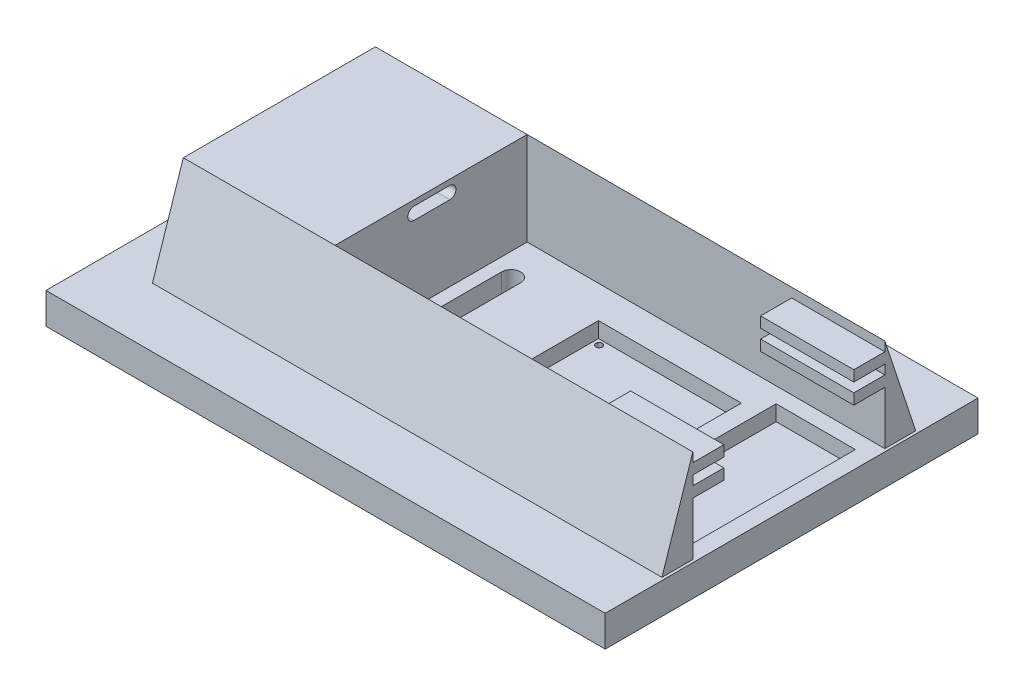
SolidWorks part; units mm, degrees
ref_plane "Front Plane" through (0, 0, 0) normal (0, 0, 1) x (1, 0, 0)
ref_plane "Top Plane" through (0, 0, 0) normal (0, 1, 0) x (1, 0, 0)
ref_plane "Right Plane" through (0, 0, 0) normal (1, 0, 0) x (0, 0, -1)
sketch "Sketch1" plane through (0, 0, 0) normal (0, 1, 0) x (1, 0, 0)
  line L1 (90, 60) -> (-90, 60)
  line L2 (90, 60) -> (90, -60)
  line L3 (90, -60) -> (-90, -60)
  line L4 (-90, 60) -> (-90, -60)
  line L5 (90, 60) -> (-90, -60) construction
  line L6 (90, -60) -> (-90, 60) construction
  point P0 (0, 0)
  dimension "D1" = 120
  dimension "D2" = 180
extrude "Boss-Extrude1" add sketch "Sketch1" along normal blind 10
sketch "Sketch2" plane through (0, 10, 0) normal (0, 1, 0) x (1, 0, 0)
  line L1 (-26.0439, 30.9093) -> (-74.8883, 30.9093)
  line L2 (-26.0439, 30.9093) -> (-26.0439, -30.9093)
  line L3 (-26.0439, -30.9093) -> (-74.8883, -30.9093)
  line L4 (-74.8883, 30.9093) -> (-74.8883, -30.9093)
  line L5 (-26.0439, 30.9093) -> (-74.8883, -30.9093) construction
  line L6 (-26.0439, -30.9093) -> (-74.8883, 30.9093) construction
  point P0 (-50.4661, 0)
extrude "Boss-Extrude2" add sketch "Sketch2" along normal blind 30
sketch "Sketch3" plane through (-74.8883, 0, 0) normal (-1, 0, 0) x (0, 0, 1)
  line L0 (30.9093, 25) -> (0, 25) construction
  line L1 (30.9093, 40) -> (30.9093, 10) construction
  line L3 (13.5, 38.5) -> (-13.5, 38.5)
  line L4 (13.5, 38.5) -> (13.5, 11.5)
  line L5 (13.5, 11.5) -> (-13.5, 11.5)
  line L6 (-13.5, 38.5) -> (-13.5, 11.5)
  line L7 (13.5, 38.5) -> (-13.5, 11.5) construction
  line L8 (13.5, 11.5) -> (-13.5, 38.5) construction
  dimension "D1" = 27
  dimension "D2" = 27
extrude "Cut-Extrude1" cut sketch "Sketch3" against normal blind 10
sketch "Sketch4" plane through (-64.8883, 0, 0) normal (-1, 0, 0) x (0, 0, 1)
  line L0 (-6.0245, 37.2243) -> (5.5495, 37.2243) construction
  line L1 (-6.0245, 38.2264) -> (5.5495, 38.2264)
  line L2 (-6.0245, 36.2222) -> (5.5495, 36.2222)
  arc A0 (-6.0245, 38.2264) -> (-6.0245, 36.2222) centre (-6.0245, 37.2243) ccw
  arc A1 (5.5495, 36.2222) -> (5.5495, 38.2264) centre (5.5495, 37.2243) ccw
  point P2 (-0.2375, 37.2243)
extrude "Cut-Extrude5" cut sketch "Sketch4" against normal through all
hole_wizard "Tap Drill for M2.5 Tap1" positions "3DSketch2" profile "Sketch8" hole size "M2.5" standard "AS"
sketch3d "3DSketch2"
  point P0 (-64.8883, 36.9534, -12.0704)
  point P2 (-64.8883, 37.0029, 11.9892)
  point P4 (-64.8883, 13.0898, 11.9186)
  point P6 (-64.8883, 13.0898, -11.8428)
sketch "Sketch8" plane through (-64.8883, 36.9534, -12.0704) normal (0, 1, 0) x (0, 0, 1)
  line L0 (0, 0) -> (0, 5.6159)
  line L1 (0, 5.6159) -> (1.025, 5)
  line L2 (1.025, 5) -> (1.025, 0.0241)
  line L3 (1.025, 0.0241) -> (1.05, 0)
  line L5 (1.05, 0) -> (0, 0)
  line L6 (-1.025, 0.0241) -> (-1.05, 0) construction
  line L10 (0, 5.6159) -> (-1.025, 5) construction
  line L11 (0, -6.35) -> (0, 107.95) construction
  dimension "Hole Dia." = 2.05
  dimension "Hole Depth" = 5
  dimension "Near C'Sink Dia." = 2.1
  dimension "Near C'Sink Angle" = 92
  dimension "Drill Angle" = 118
sketch "Sketch9" plane through (0, 10, 0) normal (0, 1, 0) x (1, 0, 0)
  line L0 (-18.7936, -19.0798) -> (-18.7936, 18.5074) construction
  line L1 (-21.8464, -19.0798) -> (-21.8464, 18.5074)
  line L2 (-15.7408, -19.0798) -> (-15.7408, 18.5074)
  arc A0 (-21.8464, -19.0798) -> (-15.7408, -19.0798) centre (-18.7936, -19.0798) ccw
  arc A1 (-15.7408, 18.5074) -> (-21.8464, 18.5074) centre (-18.7936, 18.5074) ccw
  point P2 (-18.7936, -0.2862)
extrude "Cut-Extrude6" cut sketch "Sketch9" against normal through all
sketch "Sketch10" plane through (-74.8883, 0, 0) normal (-1, 0, 0) x (0, 0, 1)
  line L0 (30.9093, 10) -> (30.9093, 40)
  line L1 (30.9093, 40) -> (40.8472, 10)
  line L2 (-60, 10) -> (60, 10) construction
  line L3 (40.8472, 10) -> (30.9093, 10)
extrude "Boss-Extrude3" add sketch "Sketch10" against normal blind 49
mirror "Mirror2" about plane through (0, 0, 0) normal (0, 0, 1) of "Boss-Extrude3"
sketch "Sketch13" plane through (-25.8883, 0, 0) normal (1, 0, 0) x (0, 0, -1)
  line L0 (-30.9093, 10) -> (-40.8472, 10)
  line L1 (-60, 10) -> (60, 10) construction
  line L2 (-30.9093, 10) -> (-40.8472, 10) construction
  line L3 (-40.8472, 10) -> (-30.9093, 40)
  line L4 (-30.9093, 40) -> (-30.9093, 10)
sketch "Sketch14" plane through (0, 10, 0) normal (0, 1, 0) x (1, 0, 0)
  line L1 (53.3281, 20.5) -> (7.3281, 20.5)
  line L2 (53.3281, 20.5) -> (53.3281, -20.5)
  line L3 (53.3281, -20.5) -> (7.3281, -20.5)
  line L4 (7.3281, 20.5) -> (7.3281, -20.5)
  line L5 (53.3281, 20.5) -> (7.3281, -20.5) construction
  line L6 (53.3281, -20.5) -> (7.3281, 20.5) construction
  point P0 (30.3281, 0)
  dimension "D1" = 46
  dimension "D2" = 41
extrude "Cut-Extrude8" cut sketch "Sketch14" against normal blind 5
hole_wizard "Tap Drill for M2.5 Tap2" positions "3DSketch3" profile "Sketch17" hole size "M2.5" standard "AS"
sketch3d "3DSketch3"
  point P0 (9.5536, 5, 18.1965)
  point P2 (9.2777, 5, -18.7664)
  point P4 (51.5506, 5, -18.3527)
  point P6 (51.5506, 5, 18.7481)
sketch "Sketch17" plane through (9.5536, 5, 18.1965) normal (1, 0, 0) x (0, 0, 1)
  line L0 (0, 0) -> (0, 5.6159)
  line L1 (0, 5.6159) -> (1.025, 5)
  line L2 (1.025, 5) -> (1.025, 0.0241)
  line L3 (1.025, 0.0241) -> (1.05, 0)
  line L5 (1.05, 0) -> (0, 0)
  line L6 (-1.025, 0.0241) -> (-1.05, 0) construction
  line L10 (0, 5.6159) -> (-1.025, 5) construction
  line L11 (0, -6.35) -> (0, 107.95) construction
  dimension "Hole Dia." = 2.05
  dimension "Hole Depth" = 5
  dimension "Near C'Sink Dia." = 2.1
  dimension "Near C'Sink Angle" = 92
  dimension "Drill Angle" = 118
sketch "Sketch18" plane through (-25.8883, 0, 0) normal (1, 0, 0) x (0, 0, -1)
  line L0 (40.8472, 10) -> (30.9093, 10)
  line L1 (30.9093, 10) -> (30.9093, 40)
  line L2 (30.9093, 40) -> (40.8472, 10)
extrude "Boss-Extrude5" add sketch "Sketch18" along normal blind 115
sketch "Sketch19" plane through (-25.8883, 0, 0) normal (1, 0, 0) x (0, 0, -1)
  line L0 (-30.9093, 10) -> (-40.8472, 10)
  line L1 (-40.8472, 10) -> (-30.9093, 40)
  line L2 (-30.9093, 40) -> (-30.9093, 10)
extrude "Boss-Extrude6" add sketch "Sketch19" along normal blind 115
sketch "Sketch25" plane through (0, 0, 0) normal (0, -1, 0) x (1, 0, 0)
  line L0 (-90, 60) -> (-90, 55)
  line L1 (-90, -60) -> (-90, 60) construction
  line L2 (-90, 55) -> (-85, 55)
  line L3 (90, 60) -> (90, 55)
  line L4 (90, 60) -> (90, -60) construction
  line L5 (90, 55) -> (85, 55)
  line L6 (90, -60) -> (90, -55)
  line L7 (90, -55) -> (85, -55)
  line L8 (-90, -60) -> (-90, -55)
  line L9 (-90, -55) -> (-85, -55)
  circle A0 centre (-85, -55) radius 2
  circle A1 centre (-85, 55) radius 2
  circle A2 centre (85, 55) radius 2
  circle A3 centre (85, -55) radius 2
  dimension "D9" = 4
  dimension "D10" = 4
  dimension "D11" = 4
  dimension "D12" = 4
  dimension "D1" = 5
  dimension "D2" = 5
  dimension "D3" = 5
  dimension "D4" = 5
  dimension "D5" = 5
  dimension "D6" = 5
  dimension "D7" = 5
  dimension "D8" = 5
sketch "Sketch26" plane through (0, 13.182, -39.7931) normal (0, 0.3145, -0.9493) x (-1, 0, 0)
  line L0 (-89.1117, 28.2512) -> (26.0439, 28.2512)
  dimension "D1" = 115.1557
sketch "Sketch27" plane through (-26.0439, 0, 0) normal (1, 0, 0) x (0, 0, -1)
  line L0 (0, 38.2264) -> (0, 40)
  line L1 (-5.5495, 38.2264) -> (6.0245, 38.2264) construction
  line L2 (-30.9093, 40) -> (30.9093, 40) construction
  dimension "D1" = 1.7736
sketch "Sketch29" plane through (0, 0, 30.9093) normal (0, 0, -1) x (-1, 0, 0)
  line L0 (-89.1117, 40) -> (-89.1117, 37)
  line L1 (-89.1117, 10) -> (-89.1117, 40) construction
  line L2 (-89.1117, 33.55) -> (-89.1117, 30.55)
  line L3 (-89.1117, 37) -> (-59.1117, 37)
  line L4 (-89.1117, 37) -> (-89.1117, 33.55)
  line L5 (-89.1117, 33.55) -> (-59.1117, 33.55)
  line L6 (-59.1117, 37) -> (-59.1117, 33.55)
  line L8 (-89.1117, 30.55) -> (-59.1117, 30.55)
  line L9 (-89.1117, 30.55) -> (-89.1117, 27.1)
  line L10 (-89.1117, 27.1) -> (-59.1117, 27.1)
  line L11 (-59.1117, 30.55) -> (-59.1117, 27.1)
  line M9 (-89.1117, 40) -> (-89.1117, 10)
  dimension "D1" = 3
  dimension "D2" = 30
  dimension "D3" = 3.45
  dimension "D4" = 3
  dimension "D5" = 3.45
  dimension "D6" = 30
extrude "Boss-Extrude10" add sketch "Sketch29" along normal blind 10 contours L6 L3 L5 M9 | L11 L8 L10 M9
mirror "Mirror3" about plane through (0, 0, 0) normal (0, 0, 1) of "Boss-Extrude10"
sketch "Sketch34" plane through (0, 0, 0) normal (0, -1, 0) x (1, 0, 0)
  circle A0 centre (-85, 55) radius 2
extrude "Cut-Extrude10" cut sketch "Sketch34" against normal blind 5
extrude "Cut-Extrude11" cut sketch "Sketch25" against normal blind 5
sketch "Sketch35" plane through (0, 0, 0) normal (0, -1, 0) x (1, 0, 0)
  line L0 (90, -60) -> (90, -55)
  line L1 (90, 60) -> (90, -60) construction
  line L2 (90, -55) -> (85, -55)
  dimension "D1" = 5
  dimension "D2" = 5
mirror "Mirror4" about plane through (0, 0, 0) normal (0, 0, 1) of "Cut-Extrude10", "Cut-Extrude11"
sketch "Sketch36" plane through (0, 10, 0) normal (0, 1, 0) x (1, 0, 0)
  line L0 (59.1117, 20.9093) -> (59.1117, 30.9093) construction
  line L1 (59.1117, 25.9093) -> (84.619, 25.9093)
  line L2 (59.1117, 25.9093) -> (59.1117, -25.9093)
  line L3 (59.1117, -25.9093) -> (84.619, -25.9093)
  line L4 (84.619, 25.9093) -> (84.619, -25.9093)
extrude "Cut-Extrude12" cut sketch "Sketch36" against normal blind 5
sketch "Sketch39" plane through (-64.8883, 0, 0) normal (-1, 0, 0) x (0, 0, 1)
  line L0 (-6.0245, 36.2222) -> (5.5495, 36.2222) construction
  line L1 (-6.0245, 38.1956) -> (5.5495, 38.1956)
  line L2 (-6.0245, 34.2489) -> (5.5495, 34.2489)
  arc A0 (-6.0245, 38.1956) -> (-6.0245, 34.2489) centre (-6.0245, 36.2222) ccw
  arc A1 (5.5495, 34.2489) -> (5.5495, 38.1956) centre (5.5495, 36.2222) ccw
  point P4 (-0.2375, 36.2222)
extrude "Cut-Extrude14" cut sketch "Sketch39" against normal through all
